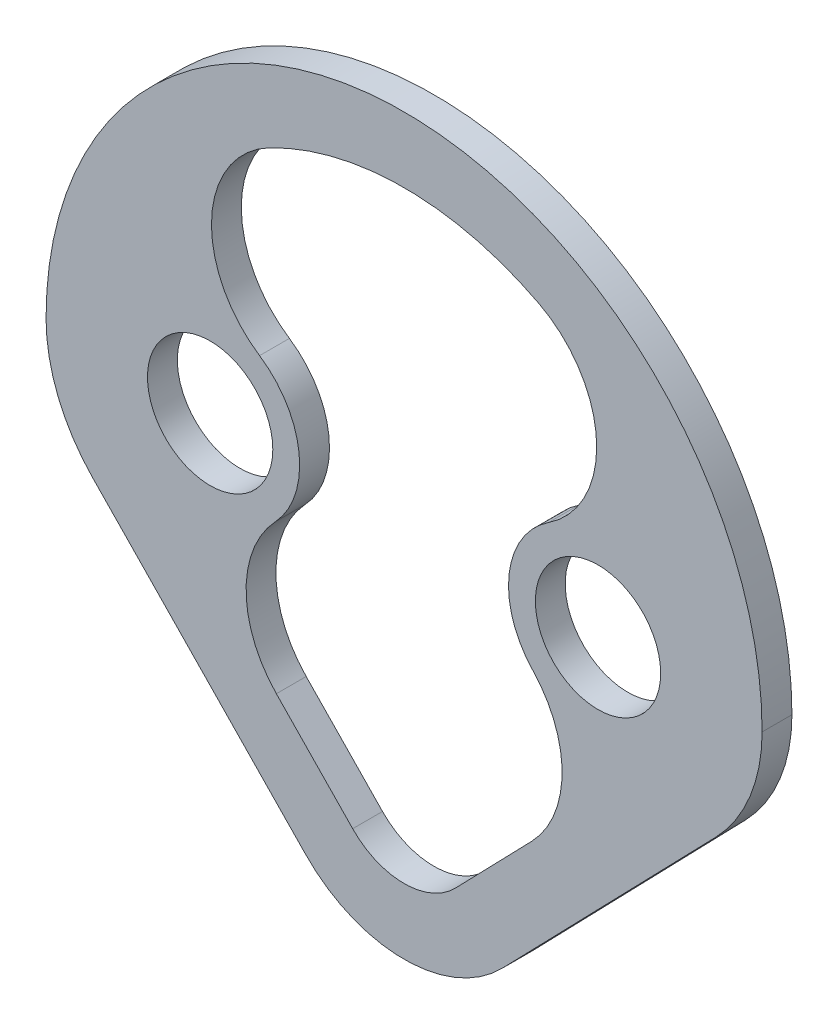
SolidWorks part; units mm, degrees
ref_plane "Front Plane" through (0, 0, 0) normal (0, 0, 1) x (1, 0, 0)
ref_plane "Top Plane" through (0, 0, 0) normal (0, 1, 0) x (1, 0, 0)
ref_plane "Right Plane" through (0, 0, 0) normal (1, 0, 0) x (0, 0, -1)
sketch "Sketch2" plane through (0, 0, 0) normal (0, 0, 1) x (1, 0, 0)
  line L0 (16.5161, -16.0068) -> (52.2475, 20.8614)
  line L1 (0, -55) -> (0, 55) construction
  line L3 (21.4059, 4.8443) -> (8.6171, -8.3514)
  line L4 (-21.4059, 4.8443) -> (-8.6171, -8.3514)
  line L5 (-16.5161, -16.0068) -> (-52.2475, 20.8614)
  arc A1 (-16.5161, -16.0068) -> (16.5161, -16.0068) centre (0, 0) ccw
  circle A2 centre (-32.5, 40) radius 10.5
  circle A3 centre (32.5, 40) radius 10.5
  arc A4 (60, 40) -> (-60, 40) centre (0, 40) ccw
  arc A5 (22.5728, 83.491) -> (-22.5728, 83.491) centre (0, 40) ccw
  arc A6 (49, 40) -> (-49, 40) centre (0, 40) ccw construction
  arc A7 (22.5728, 83.491) -> (24.2185, 52.5067) centre (14.2808, 67.5147) cw
  arc A8 (24.2185, 52.5067) -> (21.5819, 29.7143) centre (32.5, 40) ccw
  arc A10 (21.5819, 29.7143) -> (21.4059, 4.8443) centre (8.4803, 17.3714) cw
  arc A11 (-8.6171, -8.3514) -> (8.6171, -8.3514) centre (0, 0) ccw
  arc A12 (-21.5819, 29.7143) -> (-21.4059, 4.8443) centre (-8.4803, 17.3714) ccw
  arc A13 (-24.2185, 52.5067) -> (-21.5819, 29.7143) centre (-32.5, 40) cw
  arc A14 (-22.5728, 83.491) -> (-24.2185, 52.5067) centre (-14.2808, 67.5147) ccw
  arc A15 (-22.5728, 83.491) -> (22.5728, 83.491) centre (0, 40) cw
  arc A17 (60, 40) -> (-60, 40) centre (0, 40) ccw construction
  arc A18 (52.2475, 20.8614) -> (60, 40) centre (32.5, 40) ccw
  arc A19 (-52.2475, 20.8614) -> (-60, 40) centre (-32.5, 40) cw
  point P24 (0, 0)
  point P27 (0, 0)
  dimension "D1" = 60
  dimension "D3" = 46
  dimension "D5" = 21
  dimension "D7" = 18
  dimension "D8" = 15
  dimension "D9" = 27.5
  dimension "D10" = 18
  dimension "D11" = 24
  dimension "D2" = 40
  dimension "D4" = 32.5
  dimension "D6" = 11
extrude "Boss-Extrude1" add sketch "Sketch2" along normal blind 5 contours A4 A19 L5 A1 L0 A18 A3 A2 A14 A5 A7 A8 A10 L3 A11 L4 A12 A13
